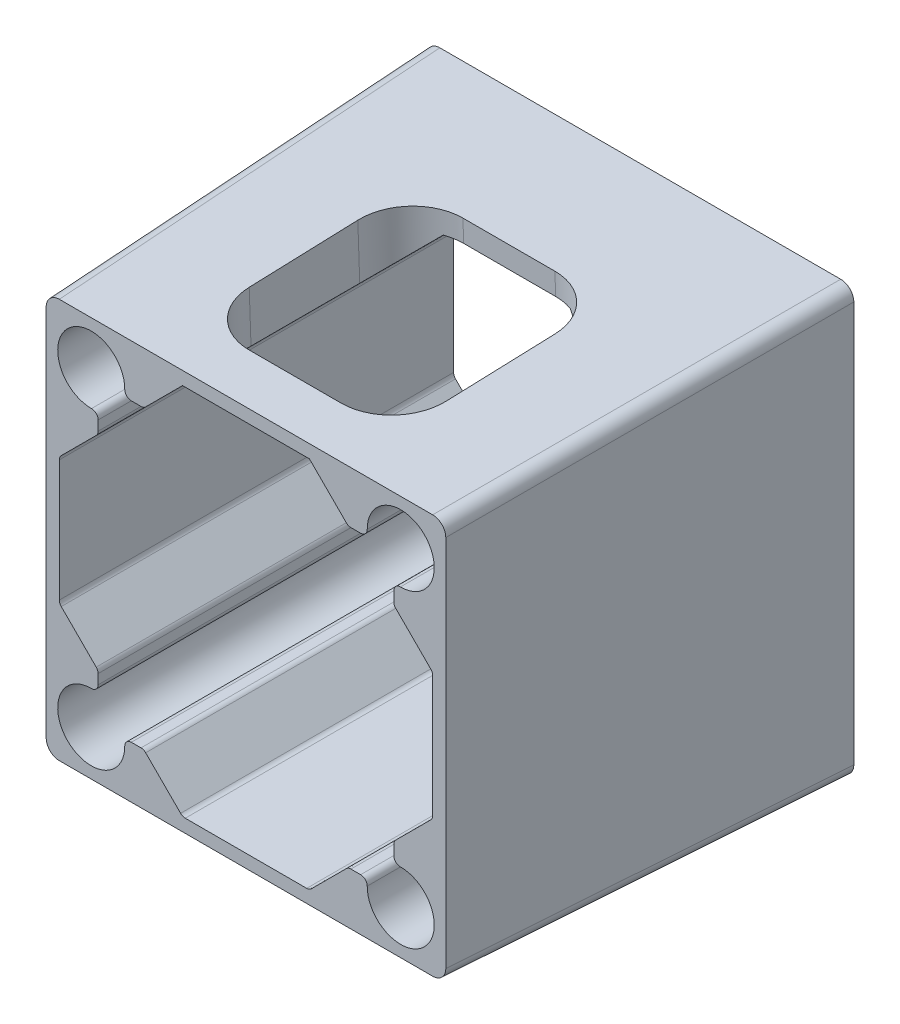
SolidWorks part; units mm, degrees
material "ABS"
ref_plane "Front Plane" through (0, 0, 0) normal (0, 0, 1) x (1, 0, 0)
ref_plane "Top Plane" through (0, 0, 0) normal (0, 1, 0) x (1, 0, 0)
ref_plane "Right Plane" through (0, 0, 0) normal (1, 0, 0) x (0, 0, -1)
sketch "Sketch1" plane through (0, 0, 0) normal (0, 0, 1) x (1, 0, 0)
  line L1 (32.5, -32.5) -> (-32.5, -32.5)
  line L2 (32.5, -32.5) -> (32.5, 32.5)
  line L3 (32.5, 32.5) -> (-32.5, 32.5)
  line L4 (-32.5, -32.5) -> (-32.5, 32.5)
  line L5 (32.5, -32.5) -> (-32.5, 32.5) construction
  line L6 (32.5, 32.5) -> (-32.5, -32.5) construction
  point P0 (0, 0)
  dimension "D1" = 65
  dimension "D2" = 65
extrude "Boss-Extrude1" add sketch "Sketch1" along normal blind 60 draft 2
sketch "Sketch4" plane through (0, 0, 60) normal (0, 0, 1) x (1, 0, 0)
  line L0 (-23.5502, 23.5502) -> (0, 0) construction
  line L1 (0, 0) -> (0, 33.305) construction
  circle A0 centre (0, 0) radius 33.305 construction
  circle A1 centre (-23.5502, 23.5502) radius 5.1
  circle A2 centre (23.5502, 23.5502) radius 5.1
  circle A3 centre (23.5502, -23.5502) radius 5.1
  circle A4 centre (-23.5502, -23.5502) radius 5.1
  point P15 (0, 0)
  dimension "D1" = 66.61
  dimension "D2" = 10.2
  dimension "D3" = 45
  dimension "D4" = 4
extrude "Cut-Extrude1" cut sketch "Sketch4" against normal up to next
sketch "Sketch5" plane through (0, 0, 60) normal (0, 0, 1) x (1, 0, 0)
  line L1 (22.5, -22.5) -> (-22.5, -22.5)
  line L2 (22.5, -22.5) -> (22.5, 22.5)
  line L3 (22.5, 22.5) -> (-22.5, 22.5)
  line L4 (-22.5, -22.5) -> (-22.5, 22.5)
  line L5 (22.5, -22.5) -> (-22.5, 22.5) construction
  line L6 (22.5, 22.5) -> (-22.5, -22.5) construction
  point P0 (0, 0)
  dimension "D1" = 45
  dimension "D2" = 45
extrude "Cut-Extrude2" cut sketch "Sketch5" against normal up to next
sketch "Sketch6" plane through (0, 0, 60) normal (0, 0, 1) x (1, 0, 0)
  line L0 (-22.5, -15.5595) -> (-22.5, 15.5595)
  line L5 (-15.5595, 22.5) -> (15.5595, 22.5)
  line L6 (-30.4048, 30.4048) -> (-30.4048, -30.4048) construction
  line L7 (-22.5, -15.5595) -> (-28.4048, -9.6547)
  line L8 (-22.5, 18.5595) -> (-22.5, -18.5595) construction
  line L9 (-28.4048, -9.6547) -> (-28.4048, 9.6547)
  line L10 (-28.4048, 9.6547) -> (-22.5, 15.5595)
  line L11 (-28.4048, 0) -> (0, 0) construction
  line L12 (9.6547, 28.4048) -> (15.5595, 22.5)
  line L13 (-9.6547, 28.4048) -> (9.6547, 28.4048)
  line L14 (-15.5595, 22.5) -> (-9.6547, 28.4048)
  line L15 (22.5, 15.5595) -> (22.5, -15.5595)
  line L16 (28.4048, -9.6547) -> (22.5, -15.5595)
  line L17 (28.4048, 9.6547) -> (28.4048, -9.6547)
  line L18 (22.5, 15.5595) -> (28.4048, 9.6547)
  line L19 (0, 0) -> (-22.5, -15.5595) construction
  line L20 (0, 0) -> (-15.5595, 22.5) construction
  line L21 (15.5595, -22.5) -> (-15.5595, -22.5)
  line L22 (-9.6547, -28.4048) -> (-15.5595, -22.5)
  line L23 (9.6547, -28.4048) -> (-9.6547, -28.4048)
  line L24 (15.5595, -22.5) -> (9.6547, -28.4048)
  line L25 (-18.5595, -22.5) -> (18.5595, -22.5) construction
  line L26 (18.5595, 22.5) -> (-18.5595, 22.5) construction
  dimension "D1" = 45
  dimension "D2" = 2
  dimension "D3" = 3
  dimension "D5" = 270
  dimension "D4" = 4
extrude "Cut-Extrude4" cut sketch "Sketch6" against normal up to next
sketch "Sketch7" plane through (0, 32.4604, 1.1335) normal (0, 0.9994, 0.0349) x (1, 0, 0)
  line L0 (0, 0) -> (0, -58.9023) construction
  line L1 (30.4048, -58.9023) -> (-30.4048, -58.9023) construction
  line L2 (32.5, 1.1342) -> (-32.5, 1.1342) construction
  line L3 (15, -51.4023) -> (-15, -51.4023)
  line L4 (15, -51.4023) -> (15, -18.8658)
  line L5 (15, -18.8658) -> (-15, -18.8658)
  line L6 (-15, -51.4023) -> (-15, -18.8658)
  line L7 (15, -51.4023) -> (-15, -18.8658) construction
  line L8 (15, -18.8658) -> (-15, -51.4023) construction
  point P5 (0, -35.1341)
  dimension "D1" = 30
  dimension "D2" = 7.5
  dimension "D3" = 20
extrude "Cut-Extrude5" cut sketch "Sketch7" against normal up to next
fillet "Fillet1" radius 2 4 edges at (31.4524, -31.4524, 30) (31.4524, 31.4524, 30) (-31.4524, 31.4524, 30) (-31.4524, -31.4524, 30)
fillet "Fillet3" radius 1 22 edges at (9.6547, -28.4048, 30) (15.5595, -22.5, 30) (18.5595, -22.5, 30) (22.5, -18.5595, 30) (22.5, -15.5595, 30) (28.4048, -9.6547, 30) (-15.5595, 22.5, 30) (-18.5595, 22.5, 30) (-28.4048, 9.6547, 30) (-22.5, 15.5595, 30) (-22.5, 18.5595, 30) (-28.4048, -9.6547, 30) (-22.5, -15.5595, 30) (-22.5, -18.5595, 30) (-18.5595, -22.5, 30) (-9.6547, -28.4048, 30) (-15.5595, -22.5, 30) (15.5595, 22.5, 30) (18.5595, 22.5, 30) (22.5, 18.5595, 30) (22.5, 15.5595, 30) (28.4048, 9.6547, 30)
fillet "Fillet5" radius 8 4 edges at (15, 26.863, 52.3717) (-15, 26.863, 52.3717) (15, 27.4308, 19.8352) (-15, 27.4308, 19.8352)
